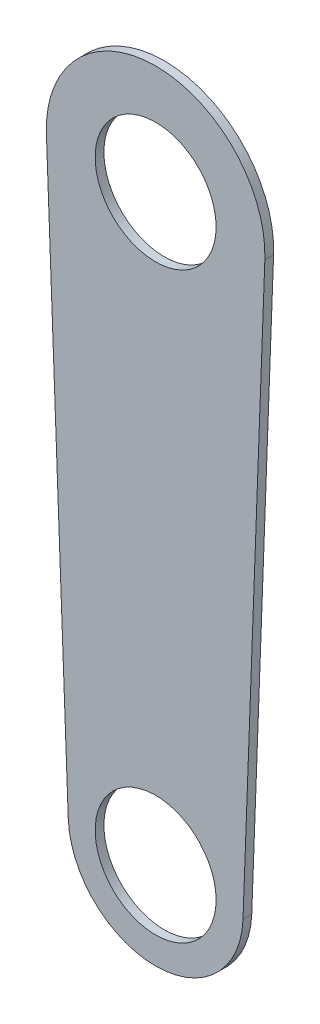
SolidWorks part; units mm, degrees
ref_plane "前视基准面" through (0, 0, 0) normal (0, 0, 1) x (1, 0, 0)
ref_plane "上视基准面" through (0, 0, 0) normal (0, 1, 0) x (1, 0, 0)
ref_plane "右视基准面" through (0, 0, 0) normal (1, 0, 0) x (0, 0, -1)
other "Configuration Table"
sketch "草图1" plane through (0, 0, 0) normal (0, 0, 1) x (1, 0, 0)
  line L0 (0, 435.7923) -> (0, -629.8791) construction
  line L1 (-74.9472, -2.8125) -> (-59.9578, -402.25)
  line L2 (74.9472, -2.8125) -> (59.9578, -402.25)
  arc A0 (74.9472, -2.8125) -> (-74.9472, -2.8125) centre (0, 0) ccw
  arc A1 (-59.9578, -402.25) -> (59.9578, -402.25) centre (0, -400) ccw
  circle A2 centre (0, 0) radius 41.5
  circle A3 centre (0, -400) radius 41.5
  point P8 (0, 0)
  dimension "D1" = 120
  dimension "D2" = 150
  dimension "D4" = 83
  dimension "D5" = 83
  dimension "D3" = 400
extrude "凸台-拉伸1" add sketch "草图1" along normal blind 6 contours L0 A3 | A3 L0 | A2 L0 | L0 A2 | L2 A1 L1 A0
equation "\"、\"=6"
